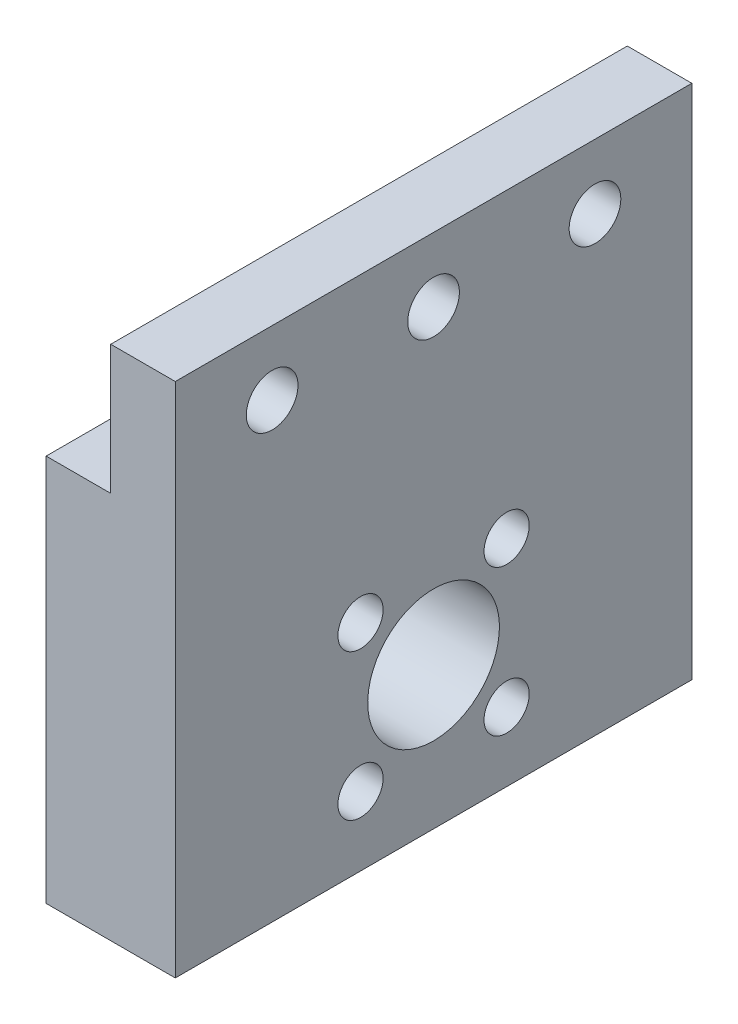
SolidWorks part; units mm, degrees
ref_plane "Front Plane" through (0, 0, 0) normal (0, 0, 1) x (1, 0, 0)
ref_plane "Top Plane" through (0, 0, 0) normal (0, 1, 0) x (1, 0, 0)
ref_plane "Right Plane" through (0, 0, 0) normal (1, 0, 0) x (0, 0, -1)
sketch "Sketch1" plane through (0, 0, 0) normal (0, 0, 1) x (1, 0, 0)
  line L0 (0, 0) -> (0, 65)
  line L1 (0, 65) -> (-50, 65)
  line L2 (-50, 65) -> (-50, 55)
  line L3 (-50, 55) -> (-10, 55)
  line L4 (-10, 55) -> (-10, 0)
  line L5 (-10, 0) -> (0, 0)
  dimension "D1" = 10
  dimension "D2" = 10
  dimension "D3" = 65
  dimension "D4" = 50
extrude "Boss-Extrude1" add sketch "Sketch1" along normal mid plane 40
sketch "Sketch2" plane through (-10, 0, 0) normal (-1, 0, 0) x (0, 0, 1)
  line L1 (-5.6569, 5.3431) -> (5.6569, 5.3431) construction
  line L2 (-5.6569, 5.3431) -> (-5.6569, 16.6569) construction
  line L3 (-5.6569, 16.6569) -> (5.6569, 16.6569) construction
  line L4 (5.6569, 5.3431) -> (5.6569, 16.6569) construction
  line L5 (-5.6569, 5.3431) -> (5.6569, 16.6569) construction
  line L6 (-5.6569, 16.6569) -> (5.6569, 5.3431) construction
  circle A0 centre (0, 11) radius 5.1
  circle A2 centre (5.6569, 16.6569) radius 1.75
  circle A3 centre (5.6569, 5.3431) radius 1.75
  circle A4 centre (-5.6569, 16.6569) radius 1.75
  circle A5 centre (-5.6569, 5.3431) radius 1.75
  dimension "D1" = 10.2
  dimension "D3" = 16
  dimension "D4" = 3.5
  dimension "D2" = 11
extrude "Cut-Extrude1" cut sketch "Sketch2" against normal through all contours A0 | A2 | A4 | A5 | A3
sketch "Sketch3" plane through (0, 0, 20) normal (0, 0, 1) x (1, 0, 0)
  line L0 (0, 0) -> (0, 65) construction
  line L1 (-50, 65) -> (0, 65)
  line L2 (-50, 65) -> (-50, 55)
  line L3 (-50, 55) -> (-10, 55)
  line L5 (-50, 55) -> (-10, 55) construction
  line L6 (-10, 55) -> (-10, 30)
  line L7 (-10, 55) -> (-10, 0) construction
  line L8 (-10, 30) -> (-5, 30)
  line L9 (-5, 30) -> (-5, 40)
  line L10 (-5, 40) -> (0, 40)
  line L11 (0, 40) -> (0, 65)
  dimension "D1" = 10
  dimension "D2" = 15
extrude "Cut-Extrude2" cut sketch "Sketch3" against normal through all
hole_wizard "Ø4.0 (4) Diameter Hole1" positions "Sketch6" profile "Sketch7" hole size "Ø4.0" standard "ISO" end condition through all
sketch "Sketch6" plane through (0, 0, 0) normal (1, 0, 0) x (0, 0, -1)
  line L0 (20, 40) -> (-20, 40) construction
  line L1 (0, 46.4946) -> (0, -13.3343) construction
  point P0 (-12.5, 35)
  point P2 (0, 35)
  point P4 (12.5, 35)
  point P19 (0, 0)
  dimension "D1" = 5
  dimension "D2" = 25
sketch "Sketch7" plane through (0, 35, 12.5) normal (0, 1, 0) x (0, 0, -1)
  line L0 (0, 0) -> (0, 10)
  line L1 (0, 10) -> (2, 10)
  line L2 (2, 10) -> (2, 0)
  line L5 (2, 0) -> (0, 0)
  line L11 (0, -6.35) -> (0, 107.95) construction
  dimension "Thru Hole Dia." = 4
  dimension "Thru Hole Depth" = 10
